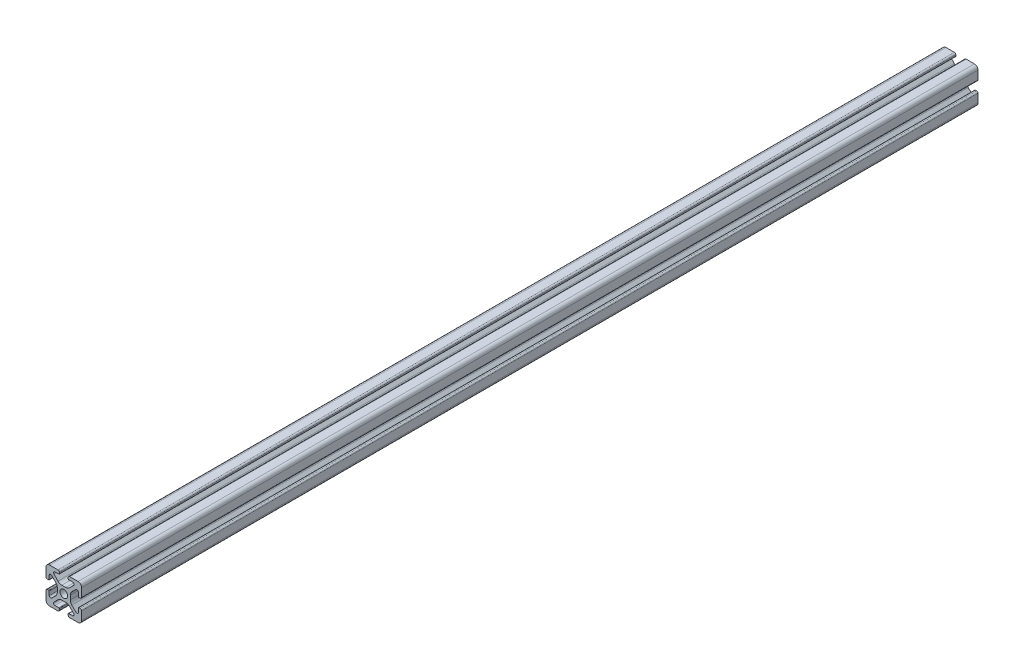
SolidWorks part; units mm, degrees
ref_plane "Plan de face" through (0, 0, 0) normal (0, 0, 1) x (1, 0, 0)
ref_plane "Plan de dessus" through (0, 0, 0) normal (0, 1, 0) x (1, 0, 0)
ref_plane "Plan de droite" through (0, 0, 0) normal (1, 0, 0) x (0, 0, -1)
ref_plane "Plan1" through (0, 0, 0) normal (0, 0, -1) x (-1, 0, 0)
sketch "Esquisse1" plane through (0, 0, 0) normal (0, 0, -1) x (-1, 0, 0)
  line L0 (-20, 6.7) -> (-20, 2)
  line L1 (-18, 0) -> (-13.3, 0)
  line L2 (-12.5, 0.8) -> (-12.5, 1.5)
  line L3 (-12.8, 1.8) -> (-14.9184, 1.8)
  line L4 (-15.5064, 3.2196) -> (-13.2547, 5.4713)
  line L5 (-11.1334, 6.35) -> (-8.8666, 6.35)
  line L6 (-6.7453, 5.4713) -> (-4.4936, 3.2196)
  line L7 (-5.0816, 1.8) -> (-7.2, 1.8)
  line L8 (-7.5, 1.5) -> (-7.5, 0.8)
  line L9 (-6.7, 0) -> (-2, 0)
  line L10 (0, 2) -> (0, 6.7)
  line L11 (-0.8, 7.5) -> (-1.5, 7.5)
  line L12 (-1.8, 7.2) -> (-1.8, 5.0816)
  line L13 (-3.2196, 4.4936) -> (-5.4713, 6.7453)
  line L14 (-6.35, 8.8666) -> (-6.35, 11.1334)
  line L15 (-5.4713, 13.2547) -> (-3.2196, 15.5064)
  line L16 (-1.8, 14.9184) -> (-1.8, 12.8)
  line L17 (-1.5, 12.5) -> (-0.8, 12.5)
  line L18 (0, 13.3) -> (0, 18)
  line L19 (-2, 20) -> (-6.7, 20)
  line L20 (-7.5, 19.2) -> (-7.5, 18.5)
  line L21 (-7.2, 18.2) -> (-5.0816, 18.2)
  line L22 (-4.4936, 16.7804) -> (-6.7453, 14.5287)
  line L23 (-8.8666, 13.65) -> (-11.1334, 13.65)
  line L24 (-13.2547, 14.5287) -> (-15.5064, 16.7804)
  line L25 (-14.9184, 18.2) -> (-12.8, 18.2)
  line L26 (-12.5, 18.5) -> (-12.5, 19.2)
  line L27 (-13.3, 20) -> (-18, 20)
  line L28 (-20, 18) -> (-20, 13.3)
  line L29 (-19.2, 12.5) -> (-18.5, 12.5)
  line L30 (-18.2, 12.8) -> (-18.2, 14.9184)
  line L31 (-16.7804, 15.5064) -> (-14.5287, 13.2547)
  line L32 (-13.65, 11.1334) -> (-13.65, 8.8666)
  line L33 (-14.5287, 6.7453) -> (-16.7804, 4.4936)
  line L34 (-18.2, 5.0816) -> (-18.2, 7.2)
  line L35 (-18.5, 7.5) -> (-19.2, 7.5)
  arc A0 (-19.2, 7.5) -> (-20, 6.7) centre (-19.2, 6.7) ccw
  arc A1 (-20, 2) -> (-18, 0) centre (-18, 2) ccw
  arc A2 (-13.3, 0) -> (-12.5, 0.8) centre (-13.3, 0.8) ccw
  arc A3 (-12.5, 1.5) -> (-12.8, 1.8) centre (-12.8, 1.5) ccw
  arc A4 (-14.9184, 1.8) -> (-15.5064, 3.2196) centre (-14.9184, 2.6316) cw
  arc A5 (-13.2547, 5.4713) -> (-11.1334, 6.35) centre (-11.1334, 3.35) cw
  arc A6 (-8.8666, 6.35) -> (-6.7453, 5.4713) centre (-8.8666, 3.35) cw
  arc A7 (-4.4936, 3.2196) -> (-5.0816, 1.8) centre (-5.0816, 2.6316) cw
  arc A8 (-7.2, 1.8) -> (-7.5, 1.5) centre (-7.2, 1.5) ccw
  arc A9 (-7.5, 0.8) -> (-6.7, 0) centre (-6.7, 0.8) ccw
  arc A10 (-2, 0) -> (0, 2) centre (-2, 2) ccw
  arc A11 (0, 6.7) -> (-0.8, 7.5) centre (-0.8, 6.7) ccw
  arc A12 (-1.5, 7.5) -> (-1.8, 7.2) centre (-1.5, 7.2) ccw
  arc A13 (-1.8, 5.0816) -> (-3.2196, 4.4936) centre (-2.6316, 5.0816) cw
  arc A14 (-5.4713, 6.7453) -> (-6.35, 8.8666) centre (-3.35, 8.8666) cw
  arc A15 (-6.35, 11.1334) -> (-5.4713, 13.2547) centre (-3.35, 11.1334) cw
  arc A16 (-3.2196, 15.5064) -> (-1.8, 14.9184) centre (-2.6316, 14.9184) cw
  arc A17 (-1.8, 12.8) -> (-1.5, 12.5) centre (-1.5, 12.8) ccw
  arc A18 (-0.8, 12.5) -> (0, 13.3) centre (-0.8, 13.3) ccw
  arc A19 (0, 18) -> (-2, 20) centre (-2, 18) ccw
  arc A20 (-6.7, 20) -> (-7.5, 19.2) centre (-6.7, 19.2) ccw
  arc A21 (-7.5, 18.5) -> (-7.2, 18.2) centre (-7.2, 18.5) ccw
  arc A22 (-5.0816, 18.2) -> (-4.4936, 16.7804) centre (-5.0816, 17.3684) cw
  arc A23 (-6.7453, 14.5287) -> (-8.8666, 13.65) centre (-8.8666, 16.65) cw
  arc A24 (-11.1334, 13.65) -> (-13.2547, 14.5287) centre (-11.1334, 16.65) cw
  arc A25 (-15.5064, 16.7804) -> (-14.9184, 18.2) centre (-14.9184, 17.3684) cw
  arc A26 (-12.8, 18.2) -> (-12.5, 18.5) centre (-12.8, 18.5) ccw
  arc A27 (-12.5, 19.2) -> (-13.3, 20) centre (-13.3, 19.2) ccw
  arc A28 (-18, 20) -> (-20, 18) centre (-18, 18) ccw
  arc A29 (-20, 13.3) -> (-19.2, 12.5) centre (-19.2, 13.3) ccw
  arc A30 (-18.5, 12.5) -> (-18.2, 12.8) centre (-18.5, 12.8) ccw
  arc A31 (-18.2, 14.9184) -> (-16.7804, 15.5064) centre (-17.3684, 14.9184) cw
  arc A32 (-14.5287, 13.2547) -> (-13.65, 11.1334) centre (-16.65, 11.1334) cw
  arc A33 (-13.65, 8.8666) -> (-14.5287, 6.7453) centre (-16.65, 8.8666) cw
  arc A34 (-16.7804, 4.4936) -> (-18.2, 5.0816) centre (-17.3684, 5.0816) cw
  arc A35 (-18.2, 7.2) -> (-18.5, 7.5) centre (-18.5, 7.2) ccw
  circle A36 centre (-10, 10) radius 2.15
extrude "Boss.-Extru.1" add sketch "Esquisse1" against normal blind 504
